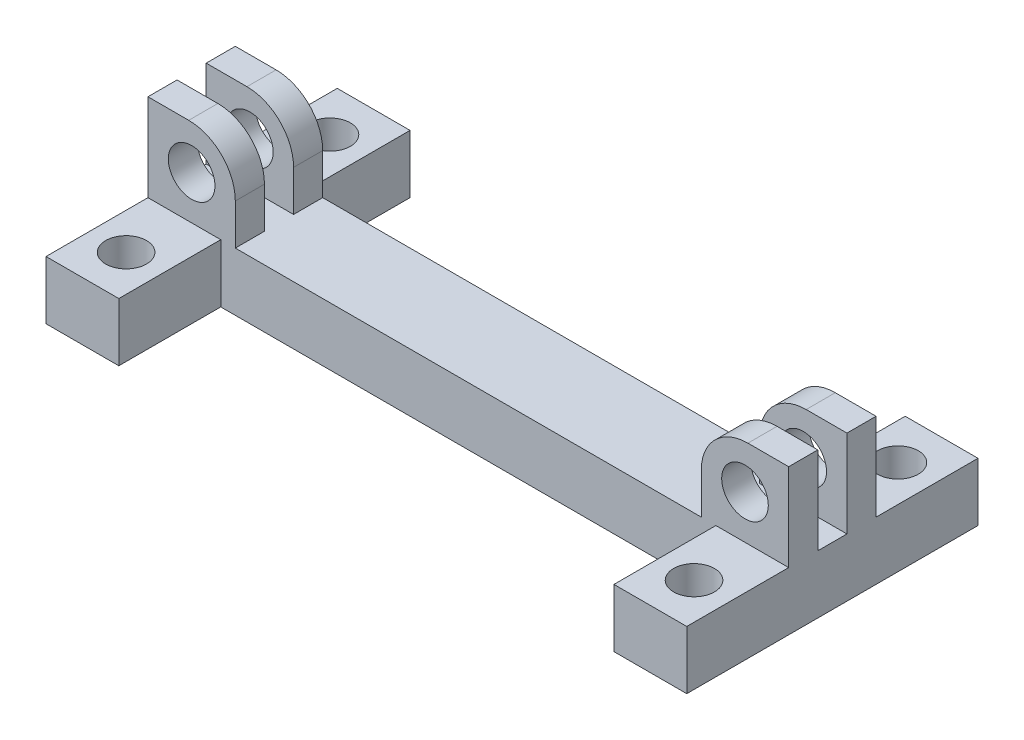
SolidWorks part; units mm, degrees
ref_plane "Front Plane" through (0, 0, 0) normal (0, 0, 1) x (1, 0, 0)
ref_plane "Top Plane" through (0, 0, 0) normal (0, 1, 0) x (1, 0, 0)
ref_plane "Right Plane" through (0, 0, 0) normal (1, 0, 0) x (0, 0, -1)
sketch "Sketch1" plane through (0, 0, 0) normal (0, 0, 1) x (1, 0, 0)
  line L0 (0, 0) -> (0, 12.7)
  line L1 (0, 0) -> (55.88, 0)
  line L5 (0, 12.7) -> (7.62, 12.7)
  line L6 (7.62, 12.7) -> (7.62, 5.08)
  line L7 (7.62, 5.08) -> (48.26, 5.08)
  line L8 (48.26, 5.08) -> (48.26, 12.7)
  line L9 (48.26, 12.7) -> (55.88, 12.7)
  line L10 (55.88, 12.7) -> (55.88, 0)
  circle A0 centre (3.81, 8.89) radius 2.032
  circle A1 centre (52.07, 8.89) radius 2.032
  point P13 (0, 0)
  point P17 (3.81, 12.7)
  dimension "D6" = 4.064
  dimension "D7" = 4.064
  dimension "D1" = 55.88
  dimension "D2" = 7.62
  dimension "D3" = 7.62
  dimension "D4" = 7.62
  dimension "D5" = 5.08
  dimension "D8" = 48.26
  dimension "D9" = 3.81
  dimension "D10" = 3.81
extrude "Boss-Extrude1" add sketch "Sketch1" against normal blind 7.62
sketch "Sketch3" plane through (55.88, 0, 0) normal (1, 0, 0) x (0, 0, -1)
  line L0 (7.62, 12.7) -> (0, 12.7) construction
  line L1 (2.54, 12.7) -> (5.08, 12.7)
  line L2 (2.54, 12.7) -> (2.54, 5.08)
  line L3 (2.54, 5.08) -> (5.08, 5.08)
  line L4 (5.08, 12.7) -> (5.08, 5.08)
  line L5 (7.62, 0) -> (0, 0) construction
  point P6 (3.81, 12.7)
  point P9 (3.81, 0)
  dimension "D1" = 7.62
  dimension "D2" = 2.54
extrude "Cut-Extrude1" cut sketch "Sketch3" against normal blind 55.88
sketch "Sketch5" plane through (0, 0, 0) normal (0, 1, 0) x (1, 0, 0)
  line L0 (55.88, 2.54) -> (55.88, 0) construction
  line L1 (55.88, 7.62) -> (49.53, 7.62)
  line L2 (55.88, 7.62) -> (55.88, 16.51)
  line L3 (55.88, 16.51) -> (49.53, 16.51)
  line L4 (49.53, 7.62) -> (49.53, 16.51)
  line L5 (55.88, 0) -> (49.53, 0)
  line L6 (55.88, 0) -> (55.88, -8.89)
  line L7 (55.88, -8.89) -> (49.53, -8.89)
  line L8 (49.53, 0) -> (49.53, -8.89)
  line L10 (0, 0) -> (6.35, 0)
  line L11 (0, 0) -> (0, -8.89)
  line L12 (0, -8.89) -> (6.35, -8.89)
  line L13 (6.35, 0) -> (6.35, -8.89)
  line L14 (0, 7.62) -> (6.35, 7.62)
  line L15 (0, 7.62) -> (0, 16.51)
  line L16 (0, 16.51) -> (6.35, 16.51)
  line L17 (6.35, 7.62) -> (6.35, 16.51)
  circle A0 centre (3.175, 12.7) radius 1.778
  circle A1 centre (52.705, 12.7) radius 1.778
  circle A2 centre (3.175, -5.08) radius 1.778
  circle A3 centre (52.705, -5.08) radius 1.778
  point P23 (0, 0)
  point P30 (0, 0)
  point P31 (52.705, -8.89)
  point P32 (0, 0)
  point P33 (0, 0)
  point P34 (52.705, 16.51)
  point P35 (0, 0)
  point P36 (0, 0)
  point P37 (3.175, -8.89)
  point P38 (3.175, 16.51)
  dimension "D4" = 3.556
  dimension "D6" = 3.81
  dimension "D1" = 6.35
  dimension "D2" = 6.35
  dimension "D3" = 8.89
  dimension "D5" = 3.81
  dimension "D7" = 3.81
  dimension "D8" = 3.81
extrude "Boss-Extrude2" add sketch "Sketch5" along normal blind 5.08
fillet "Fillet2" radius 4.064 4 edges at (48.26, 12.7, -6.35) (48.26, 12.7, -1.27) (7.62, 12.7, -6.35) (7.62, 12.7, -1.27)
